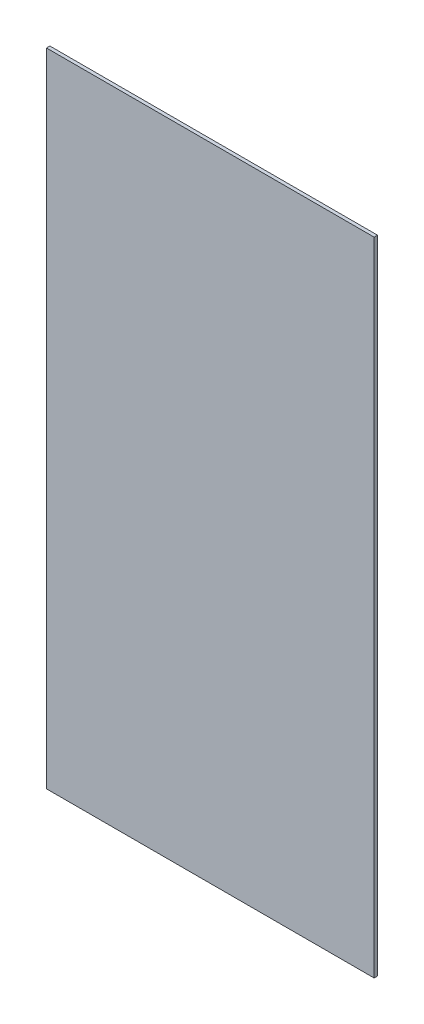
SolidWorks part; units mm, degrees
material "Гипс"
ref_plane "Спереди" through (0, 0, 0) normal (0, 0, 1) x (1, 0, 0)
ref_plane "Сверху" through (0, 0, 0) normal (0, 1, 0) x (1, 0, 0)
ref_plane "Справа" through (0, 0, 0) normal (1, 0, 0) x (0, 0, -1)
sketch "Эскиз1" plane through (0, 0, 0) normal (0, 0, 1) x (1, 0, 0)
  line L1 (0, 0) -> (-1200, 0)
  line L2 (0, 0) -> (0, 2350)
  line L3 (0, 2350) -> (-1200, 2350)
  line L4 (-1200, 0) -> (-1200, 2350)
  dimension "D1" = 1200
  dimension "D2" = 2350
extrude "Бобышка-Вытянуть1" add sketch "Эскиз1" against normal blind 12.5
sketch "Эскиз2" [suppressed] plane through (0, 0, -12.5) normal (0, 0, -1) x (-1, 0, 0)
  line L1 (600, 2090.75) -> (1200, 2090.75)
  line L2 (600, 2090.75) -> (600, 0)
  line L3 (600, 0) -> (1200, 0)
  line L4 (1200, 2090.75) -> (1200, 0)
extrude "Вырез-Вытянуть1" [suppressed] cut sketch "Эскиз2" against normal through all
sketch "Эскиз3" [suppressed] plane through (0, 0, 0) normal (0, 0, 1) x (1, 0, 0)
  line L0 (-1200, 2350) -> (-1200, 0) construction
  line L1 (-800, 1700.75) -> (-1200, 1700.75)
  line L2 (-800, 1700.75) -> (-800, 900)
  line L3 (-800, 900) -> (-1200, 900)
  line L4 (-1200, 1700.75) -> (-1200, 900)
  line L5 (-800, 900) -> (-1600, 900) construction
extrude "Вырез-Вытянуть2" [suppressed] cut sketch "Эскиз3" against normal through all
sketch "Эскиз4" [suppressed] plane through (0, 0, 0) normal (0, 0, 1) x (1, 0, 0)
  line L0 (0, 0) -> (0, 2350) construction
  line L1 (-50, 1700) -> (0, 1700)
  line L2 (-50, 1700) -> (-50, 900)
  line L3 (-50, 900) -> (0, 900)
  line L4 (0, 1700) -> (0, 900)
  line L5 (-50, 900) -> (1550, 900) construction
  line L7 (-50, 1700) -> (-50, 900) construction
extrude "Вырез-Вытянуть3" [suppressed] cut sketch "Эскиз4" against normal through all
sketch "Эскиз5" [suppressed] plane through (0, 0, 0) normal (0, 0, 1) x (1, 0, 0)
  line L0 (-1200, 2350) -> (-1200, 0) construction
  line L1 (0, 1700) -> (-1200, 1700)
  line L2 (0, 1700) -> (0, 900)
  line L3 (0, 900) -> (-1200, 900)
  line L4 (-1200, 1700) -> (-1200, 900)
  line L5 (-1250, 900) -> (350, 900) construction
extrude "Вырез-Вытянуть4" [suppressed] cut sketch "Эскиз5" against normal through all
sketch "Эскиз6" [suppressed] plane through (0, 0, 0) normal (0, 0, 1) x (1, 0, 0)
  line L1 (-700, 2091.5) -> (-1200, 2091.5)
  line L2 (-700, 2091.5) -> (-700, 0)
  line L3 (-700, 0) -> (-1200, 0)
  line L4 (-1200, 2091.5) -> (-1200, 0)
extrude "Вырез-Вытянуть5" [suppressed] cut sketch "Эскиз6" against normal through all
